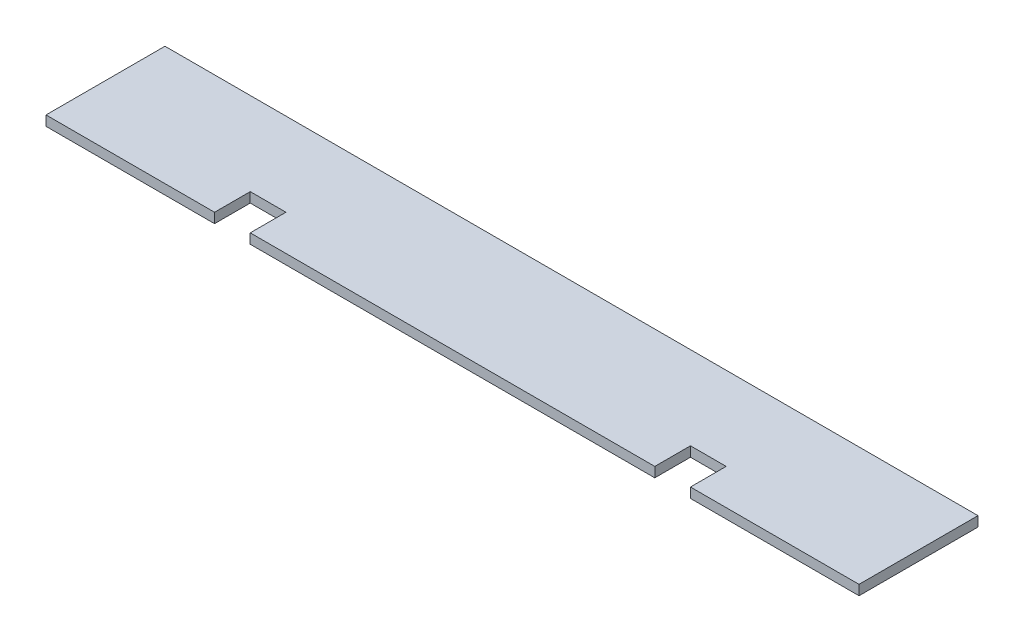
SolidWorks part; units mm, degrees
ref_plane "Front Plane" through (0, 0, 0) normal (0, 0, 1) x (1, 0, 0)
ref_plane "Top Plane" through (0, 0, 0) normal (0, 1, 0) x (1, 0, 0)
ref_plane "Right Plane" through (0, 0, 0) normal (1, 0, 0) x (0, 0, -1)
sketch "Sketch1" plane through (0, 0, 0) normal (0, 1, 0) x (1, 0, 0)
  line L1 (0, 0) -> (2050, 0)
  line L2 (0, 0) -> (0, 300)
  line L3 (0, 300) -> (2050, 300)
  line L4 (2050, 0) -> (2050, 300)
  dimension "D1" = 300
  dimension "D2" = 2050
extrude "Boss-Extrude1" add sketch "Sketch1" along normal blind 25
sketch "Sketch2" plane through (0, 25, 0) normal (0, 1, 0) x (1, 0, 0)
  line L0 (0, 0) -> (2050, 0) construction
  line L1 (425, 0) -> (515, 0)
  line L2 (425, 0) -> (425, 90)
  line L3 (425, 90) -> (515, 90)
  line L4 (515, 0) -> (515, 90)
  line L5 (0, 300) -> (0, 0) construction
  line L6 (1625, 0) -> (1535, 0)
  line L7 (1625, 0) -> (1625, 90)
  line L8 (1625, 90) -> (1535, 90)
  line L9 (1535, 0) -> (1535, 90)
  line L10 (2050, 0) -> (2050, 300) construction
  dimension "D1" = 90
  dimension "D2" = 90
  dimension "D3" = 90
  dimension "D4" = 90
  dimension "D5" = 425
  dimension "D6" = 425
extrude "Cut-Extrude1" cut sketch "Sketch2" against normal up to next
